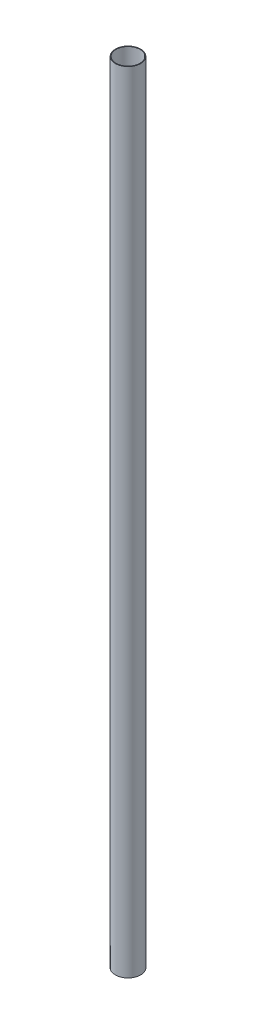
SolidWorks part; units mm, degrees
material "Wildman Fiberglass"
ref_plane "Front Plane" through (0, 0, 0) normal (0, 0, 1) x (1, 0, 0)
ref_plane "Top Plane" through (0, 0, 0) normal (0, 1, 0) x (1, 0, 0)
ref_plane "Right Plane" through (0, 0, 0) normal (1, 0, 0) x (0, 0, -1)
sketch "Sketch1" plane through (0, 0, 0) normal (0, 1, 0) x (1, 0, 0)
  circle A0 centre (0, 0) radius 19.304
  circle A1 centre (0, 0) radius 20.32
  dimension "D1" = 40.64
  dimension "D2" = 38.608
extrude "Boss-Extrude1" add sketch "Sketch1" along normal blind 1270
equation "\"Length\"= 50"
equation "\"D1@Boss-Extrude1\"=\"Length\""
